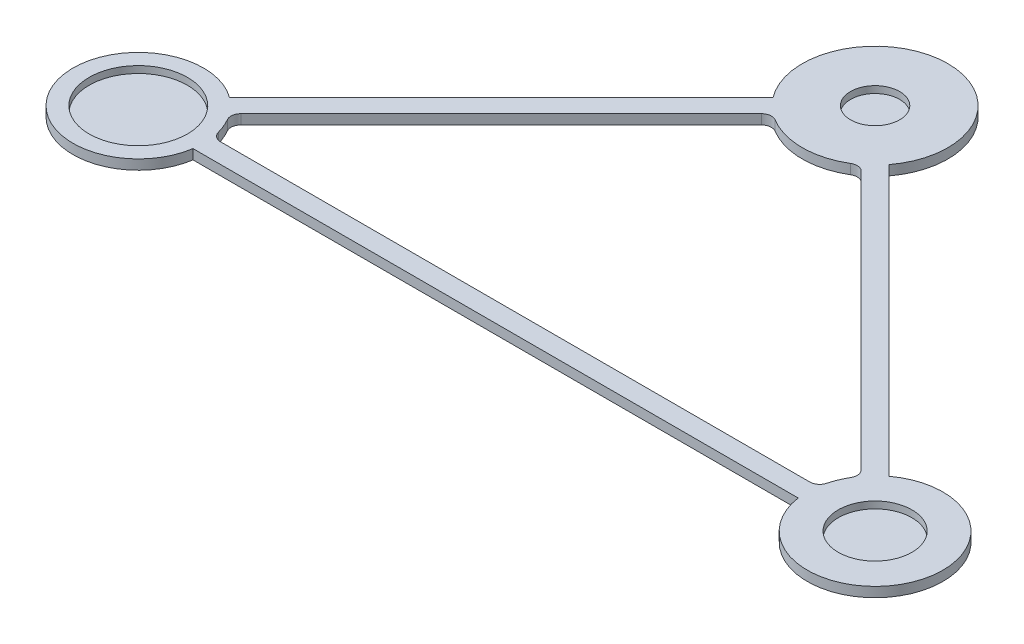
SolidWorks part; units mm, degrees
ref_plane "Ebene vorne" through (0, 0, 0) normal (0, 0, 1) x (1, 0, 0)
ref_plane "Ebene oben" through (0, 0, 0) normal (0, 1, 0) x (1, 0, 0)
ref_plane "Ebene rechts" through (0, 0, 0) normal (1, 0, 0) x (0, 0, -1)
sketch "Skizze1" plane through (0, 0, 0) normal (0, 1, 0) x (1, 0, 0)
  line L0 (0, 0) -> (0, 75) construction
  line L1 (0, 75) -> (-75, 0) construction
  line L2 (-75, 0) -> (75, 0) construction
  line L3 (0, 75) -> (75, 0) construction
  line L4 (-11.8032, 66.0252) -> (-67.1243, 10.7041)
  line L5 (-61.8621, -2) -> (61.3403, -2)
  line L6 (11.8032, 66.0252) -> (66.7553, 11.0731)
  line L7 (-8.9748, 63.1968) -> (-64.2959, 7.8757)
  line L8 (-61.8621, 2) -> (61.3403, 2)
  line L9 (8.9748, 63.1968) -> (63.9269, 8.2447)
  line L11 (0, 72.1716) -> (-70.1716, 2) construction
  line L12 (0, 77.8284) -> (-79.8284, -2) construction
  line L13 (0, 77.8284) -> (79.8284, -2) construction
  line L14 (0, 72.1716) -> (70.1716, 2) construction
  line L15 (-70.1716, 2) -> (70.1716, 2) construction
  line L16 (-79.8284, -2) -> (79.8284, -2) construction
  arc A0 (-61.8621, 2) -> (-64.2959, 7.8757) centre (-75, 0) ccw
  arc A1 (63.9269, 8.2447) -> (61.3403, 2) centre (75, 0) ccw
  arc A2 (11.8032, 66.0252) -> (-11.8032, 66.0252) centre (0, 75) ccw
  arc A5 (-8.9748, 63.1968) -> (8.9748, 63.1968) centre (0, 75) ccw
  arc A6 (-67.1243, 10.7041) -> (-61.8621, -2) centre (-75, 0) ccw
  arc A7 (61.3403, -2) -> (66.7553, 11.0731) centre (75, 0) ccw
  dimension "D1" = 90
  dimension "D2" = 150
  dimension "D3" = 2
  dimension "D4" = 2
extrude "Aufsatz-Linear austragen1" add sketch "Skizze1" along normal blind 2
sketch "Skizze2" plane through (0, 2, 0) normal (0, 1, 0) x (1, 0, 0)
  circle A0 centre (0, 75) radius 5
  circle A1 centre (-75, 0) radius 10
  circle A2 centre (75, 0) radius 7.5
  dimension "D1" = 10
  dimension "D2" = 15
  dimension "D3" = 20
extrude "Schnitt-Linear austragen1" cut sketch "Skizze2" against normal offset from surface (1.4 mm away) 0.6 up to face at (0.0052, 0, -25.7288)
fillet "Verrundung1" radius 2 6 edges at (63.9269, 1, -8.2447) (61.3403, 1, -2) (-61.8621, 1, -2) (-64.2959, 1, -7.8757) (8.9748, 1, -63.1968) (-8.9748, 1, -63.1968)
